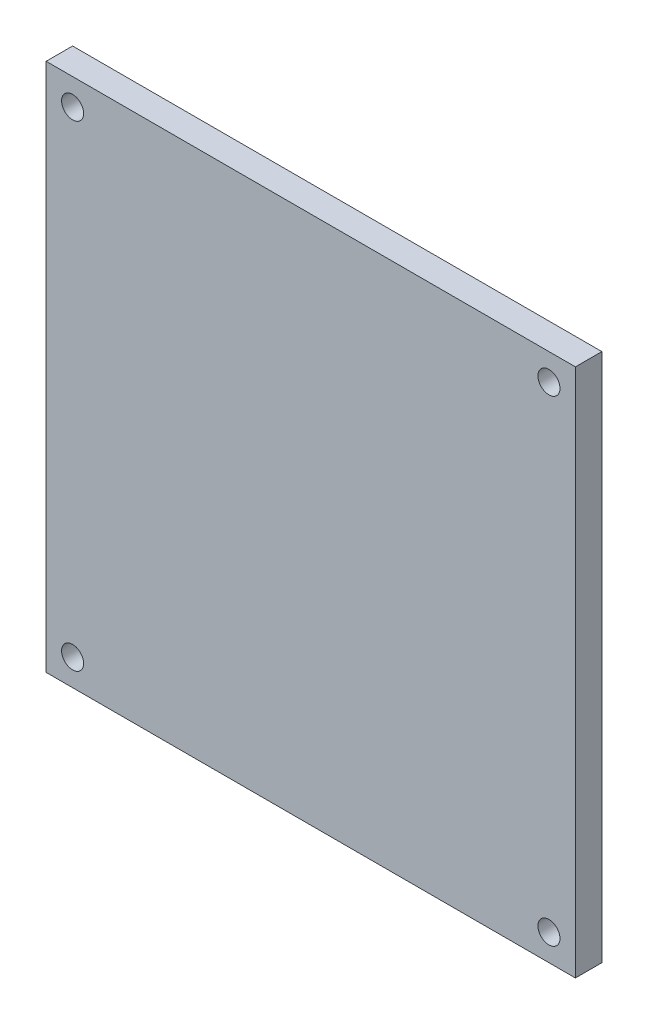
SolidWorks part; units mm, degrees
material "Aluminum"
ref_plane "Front Plane" through (0, 0, 0) normal (0, 0, 1) x (1, 0, 0)
ref_plane "Top Plane" through (0, 0, 0) normal (0, 1, 0) x (1, 0, 0)
ref_plane "Right Plane" through (0, 0, 0) normal (1, 0, 0) x (0, 0, -1)
ref_plane "Plane1" through (0, 0, -7) normal (0, 0, -1) x (-1, 0, 0)
sketch "Sketch1" plane through (0, 0, -7) normal (0, 0, -1) x (-1, 0, 0)
  line L1 (-30, -30) -> (30, -30)
  line L2 (-30, -30) -> (-30, 30)
  line L3 (-30, 30) -> (30, 30)
  line L4 (30, -30) -> (30, 30)
  line L5 (-30, -30) -> (30, 30) construction
  line L6 (-30, 30) -> (30, -30) construction
  point P0 (0, 0)
  dimension "D1" = 60
  dimension "D2" = 60
extrude "Boss-Extrude1" add sketch "Sketch1" against normal blind 3
hole_wizard "Ø2.5 (2.5) Diameter Hole1" positions "Sketch3" profile "Sketch2" hole size "Ø2.5" standard "ISO" end condition through all
sketch "Sketch3" plane through (0, 0, -4) normal (0, 0, 1) x (1, 0, 0)
  line L0 (0, 0) -> (0, 30) construction
  line L1 (-30, 30) -> (30, 30) construction
  line L4 (0, 0) -> (-30, 0) construction
  line L5 (-30, -30) -> (-30, 30) construction
  point P0 (-27, 27)
  point P2 (-27, -27)
  point P4 (27, -27)
  point P6 (27, 27)
  dimension "D1" = 27
  dimension "D2" = 27
  dimension "D3" = 27
  dimension "D4" = 27
  dimension "D5" = 27
  dimension "D6" = 27
  dimension "D7" = 27
  dimension "D8" = 27
sketch "Sketch2" plane through (-27, 27, -4) normal (1, 0, 0) x (0, -1, 0)
  line L0 (0, 0) -> (0, 3)
  line L1 (0, 3) -> (1.25, 3)
  line L2 (1.25, 3) -> (1.25, 0)
  line L5 (1.25, 0) -> (0, 0)
  line L11 (0, -6.35) -> (0, 107.95) construction
  dimension "Thru Hole Dia." = 2.5
  dimension "Thru Hole Depth" = 3
